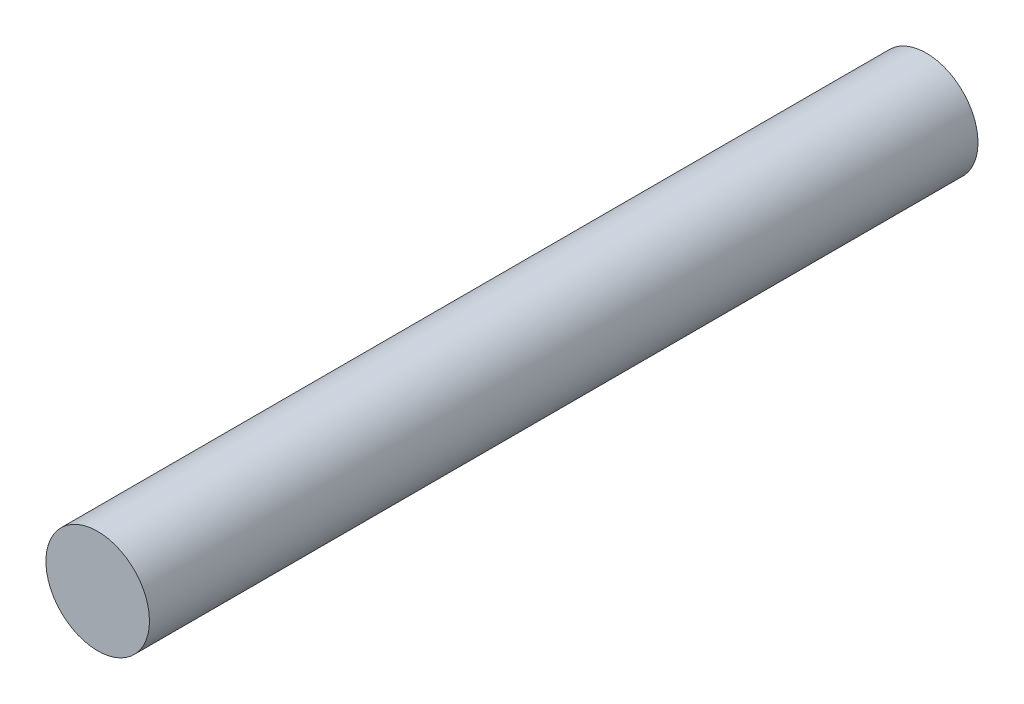
SolidWorks part; units mm, degrees
ref_plane "Front Plane" through (0, 0, 0) normal (0, 0, 1) x (1, 0, 0)
ref_plane "Top Plane" through (0, 0, 0) normal (0, 1, 0) x (1, 0, 0)
ref_plane "Right Plane" through (0, 0, 0) normal (1, 0, 0) x (0, 0, -1)
sketch "Sketch2" plane through (0, 0, 0) normal (0, 0, 1) x (1, 0, 0)
  circle A0 centre (0, 0) radius 1.5875
  dimension "D1" = 3.175
extrude "Boss-Extrude1" add sketch "Sketch2" against normal blind 25.4
